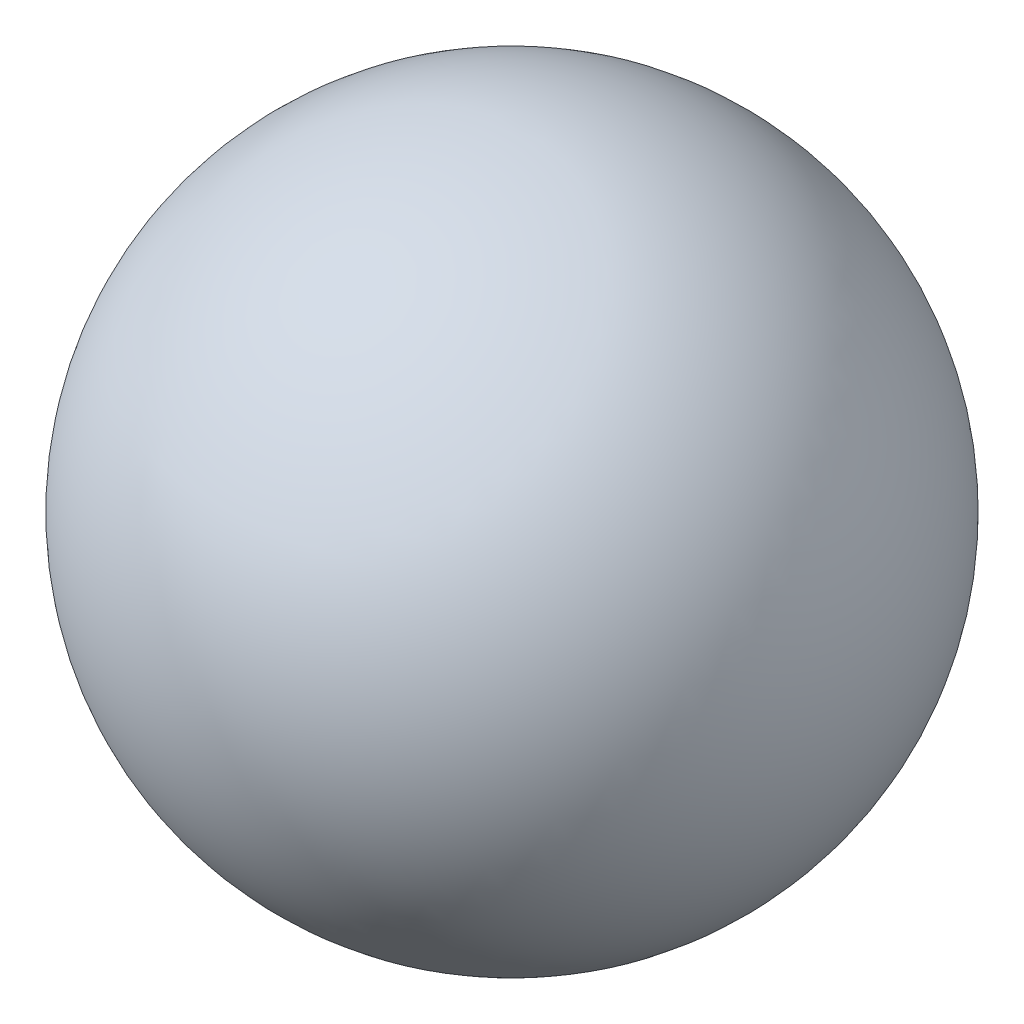
SolidWorks part; units mm, degrees
ref_plane "Plano frontal" through (0, 0, 0) normal (0, 0, 1) x (1, 0, 0)
ref_plane "Plano superior" through (0, 0, 0) normal (0, 1, 0) x (1, 0, 0)
ref_plane "Plano direito" through (0, 0, 0) normal (1, 0, 0) x (0, 0, -1)
sketch "Esboço1" plane through (0, 0, 0) normal (0, 0, 1) x (1, 0, 0)
  line L0 (0, 0) -> (48.9647, 0) construction
  line L1 (48.9647, 0) -> (-44.7391, 0) construction
  line L2 (0, 42.76) -> (0, 0) construction
  line L3 (0, 0) -> (0, 42.76)
  arc A0 (0, 0) -> (0, 42.76) centre (0, 21.38) ccw
  dimension "D1" = 42.76
revolve "Revolução1" add sketch "Esboço1" angle 360 about L3
ref_plane "Plano1" through (0, 0, 0) normal (0, 0.7071, -0.7071) x (-1, 0, 0)
ref_plane "Plano2" through (0, -4.4279, 4.4279) normal (0, 0.7071, -0.7071) x (-1, 0, 0)
ref_plane "Plano3" through (0, 42.76, 0) normal (0, 1, 0) x (1, 0, 0)
